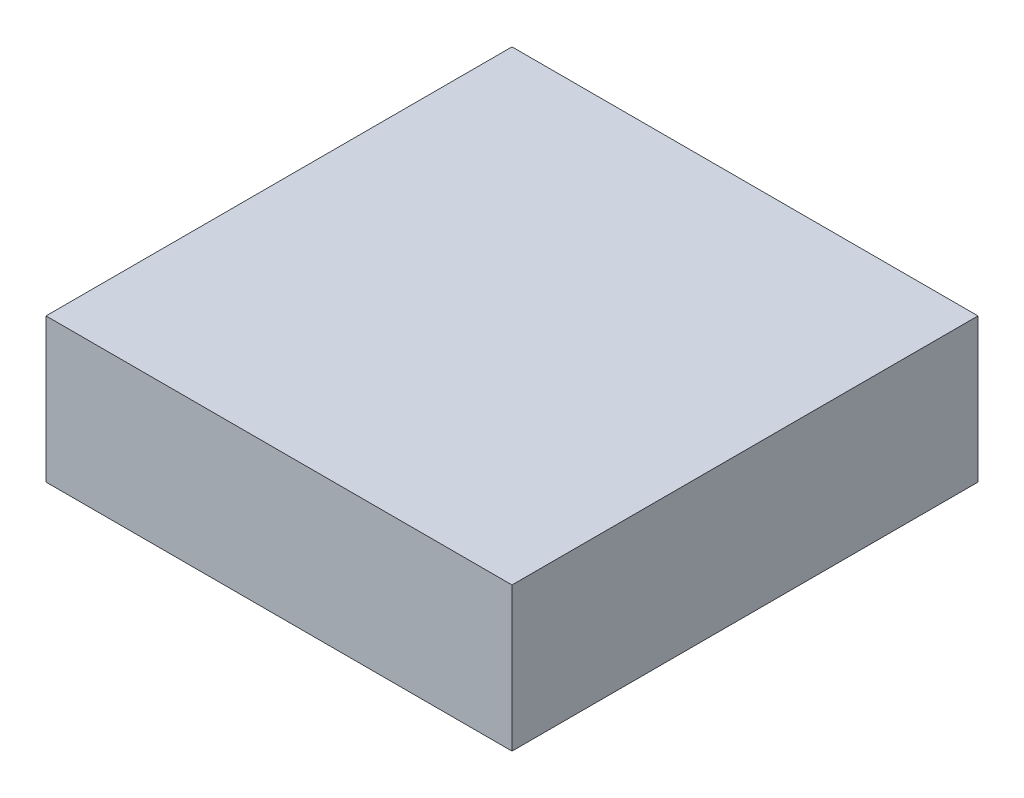
SolidWorks part; units mm, degrees
ref_plane "Front Plane" through (0, 0, 0) normal (0, 0, 1) x (1, 0, 0)
ref_plane "Top Plane" through (0, 0, 0) normal (0, 1, 0) x (1, 0, 0)
ref_plane "Right Plane" through (0, 0, 0) normal (1, 0, 0) x (0, 0, -1)
sketch "Sketch1" plane through (0, 0, 0) normal (0, 1, 0) x (1, 0, 0)
  line L1 (5.715, -5.715) -> (-5.715, -5.715)
  line L2 (5.715, -5.715) -> (5.715, 5.715)
  line L3 (5.715, 5.715) -> (-5.715, 5.715)
  line L4 (-5.715, -5.715) -> (-5.715, 5.715)
  line L5 (5.715, -5.715) -> (-5.715, 5.715) construction
  line L6 (5.715, 5.715) -> (-5.715, -5.715) construction
  point P0 (0, 0)
  dimension "D1" = 11.43
extrude "Extrude1" add sketch "Sketch1" along normal blind 3.5306
